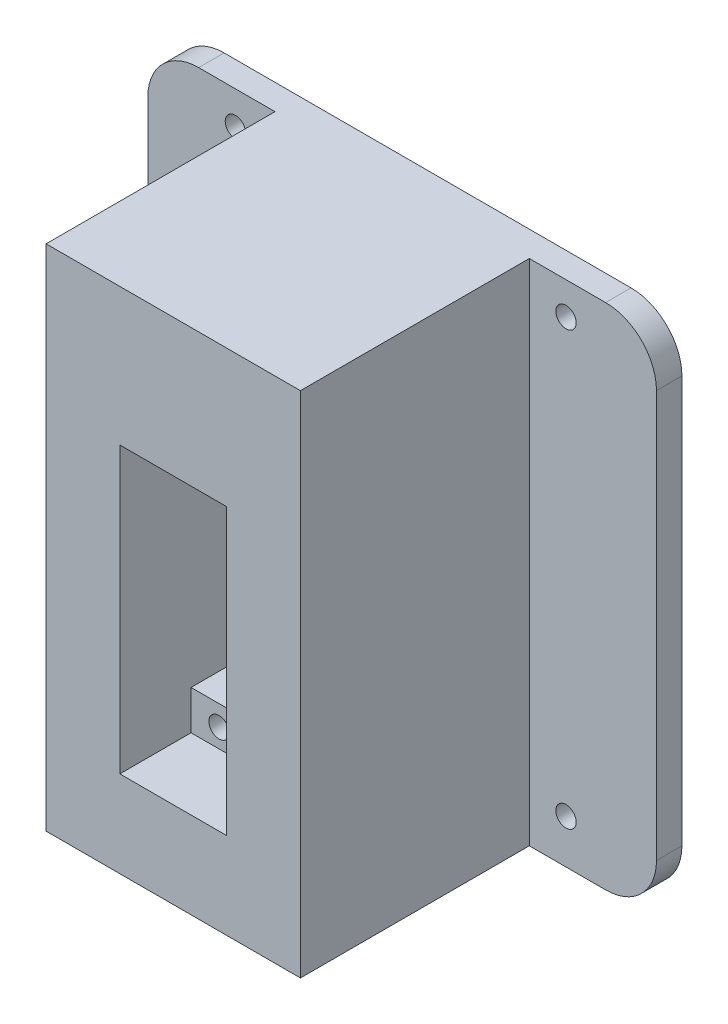
SolidWorks part; units mm, degrees
ref_plane "Front Plane" through (0, 0, 0) normal (0, 0, 1) x (1, 0, 0)
ref_plane "Top Plane" through (0, 0, 0) normal (0, 1, 0) x (1, 0, 0)
ref_plane "Right Plane" through (0, 0, 0) normal (1, 0, 0) x (0, 0, -1)
sketch "Sketch1" plane through (0, 0, 0) normal (0, 0, 1) x (1, 0, 0)
  line L1 (-40, 50) -> (40, 50)
  line L2 (-50, 40) -> (-50, -40)
  line L3 (-40, -50) -> (40, -50)
  line L4 (50, 40) -> (50, -40)
  line L5 (-50, 50) -> (50, -50) construction
  line L6 (-50, -50) -> (50, 50) construction
  arc A0 (-40, 50) -> (-50, 40) centre (-40, 40) ccw
  arc A1 (50, 40) -> (40, 50) centre (40, 40) ccw
  arc A2 (50, -40) -> (40, -50) centre (40, -40) cw
  arc A3 (-40, -50) -> (-50, -40) centre (-40, -40) cw
  point P0 (0, 0)
  dimension "D3" = 10
  dimension "D4" = 10
  dimension "D5" = 10
  dimension "D6" = 10
  dimension "D1" = 100
  dimension "D2" = 100
extrude "Boss-Extrude1" add sketch "Sketch1" along normal blind 50 contours L2 A3 L3 A2 L4 A1 L1 A0
sketch "Sketch2" plane through (0, 0, 50) normal (0, 0, 1) x (1, 0, 0)
  line L0 (0, 0) -> (0, -5) construction
  line L2 (10.5, -33) -> (-10.5, -33)
  line L3 (10.5, -33) -> (10.5, 23)
  line L4 (10.5, 23) -> (-10.5, 23)
  line L5 (-10.5, -33) -> (-10.5, 23)
  line L6 (10.5, -33) -> (-10.5, 23) construction
  line L7 (10.5, 23) -> (-10.5, -33) construction
  dimension "D1" = 56
  dimension "D2" = 21
extrude "Cut-Extrude1" cut sketch "Sketch2" against normal blind 14
sketch "Sketch3" plane through (0, 0, 36) normal (0, 0, 1) x (1, 0, 0)
  line L0 (0, 0) -> (0, -4.53) construction
  line L1 (10.5, -33) -> (10.5, 23) construction
  line L3 (-10.5, 16.22) -> (-10.5, -25.28)
  line L4 (-10.5, -25.28) -> (10.5, -25.28)
  line L5 (10.5, 16.22) -> (10.5, -25.28)
  line L6 (-10.5, 16.22) -> (10.5, -25.28) construction
  line L7 (-10.5, -25.28) -> (10.5, 16.22) construction
  line L13 (-2.75, 16.22) -> (-10.5, 16.22)
  line L14 (2.75, 16.22) -> (10.5, 16.22)
  line L16 (-2.75, 16.22) -> (-2.7714, 23.72)
  line L19 (-2.7714, 23.72) -> (2.7286, 23.72)
  line L21 (2.75, 16.22) -> (2.7286, 23.72)
  dimension "D1" = 41.5
  dimension "D2" = 41.5
  dimension "D3" = 5.5
  dimension "D4" = 5.5
  dimension "D5" = 7.75
  dimension "D6" = 7.75
extrude "Cut-Extrude2" cut sketch "Sketch3" against normal blind 40
sketch "Sketch4" plane through (0, 0, 50) normal (0, 0, 1) x (1, 0, 0)
  line L0 (-40, 50) -> (40, 50) construction
  line L1 (40, -50) -> (25, -50)
  line L2 (50, -40) -> (50, 40)
  line L3 (40, 50) -> (25, 50)
  line L4 (25, -50) -> (25, 50)
  line L6 (-40, -50) -> (-25, -50)
  line L7 (-50, -40) -> (-50, 40)
  line L8 (-40, 50) -> (-25, 50)
  line L9 (-25, -50) -> (-25, 50)
  arc A0 (-40, 50) -> (-50, 40) centre (-40, 40) ccw
  arc A1 (40, 50) -> (50, 40) centre (40, 40) cw
  arc A2 (-50, -40) -> (-40, -50) centre (-40, -40) ccw
  arc A3 (50, -40) -> (40, -50) centre (40, -40) cw
extrude "Cut-Extrude3" cut sketch "Sketch4" against normal blind 45
sketch "Sketch5" plane through (0, 0, 36) normal (0, 0, 1) x (1, 0, 0)
  line L0 (-5, 19.5) -> (-5, -29.3) construction
  line L1 (-5, -29.3) -> (5, -29.3) construction
  circle A0 centre (-5, 19.5) radius 2
  circle A1 centre (5, 19.5) radius 2
  circle A2 centre (-5, -29.3) radius 2
  circle A3 centre (5, -29.3) radius 2
  dimension "D1" = 10
  dimension "D2" = 48.8
extrude "Cut-Extrude4" cut sketch "Sketch5" against normal blind 10
sketch "Sketch6" plane through (0, 0, 5) normal (0, 0, 1) x (1, 0, 0)
  circle A0 centre (-32.7837, 43.4824) radius 2
  circle A1 centre (-32.7837, -41.5176) radius 2
  circle A2 centre (32.2163, -41.3649) radius 2
  circle A3 centre (32.2163, 43.6351) radius 2
extrude "Cut-Extrude5" cut sketch "Sketch6" against normal blind 5
